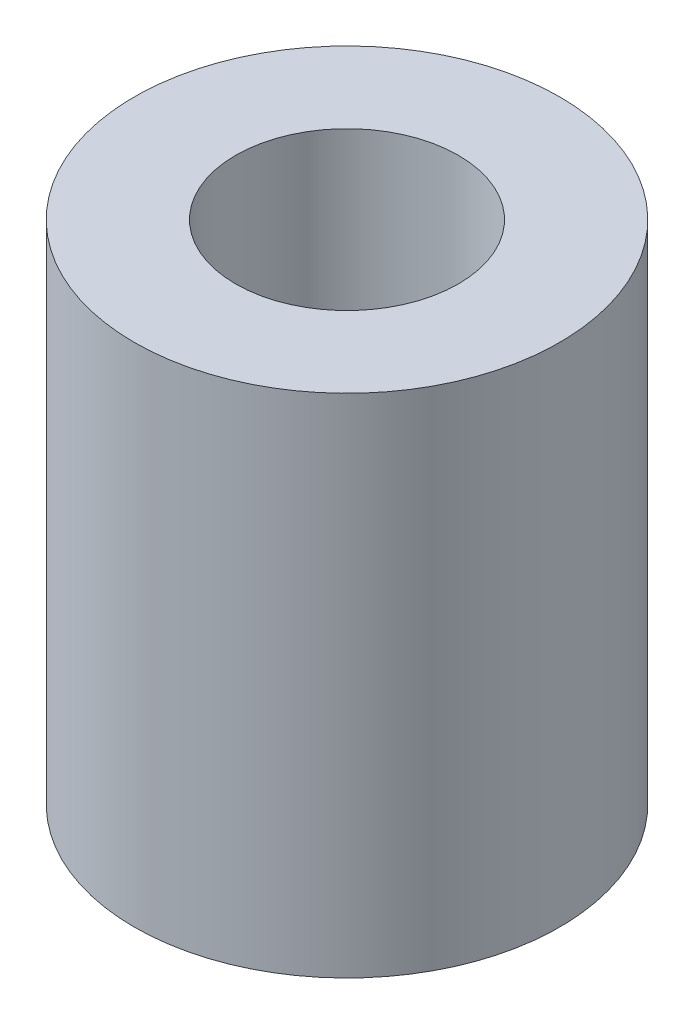
SolidWorks part; units mm, degrees
ref_plane "Front Plane" through (0, 0, 0) normal (0, 0, 1) x (1, 0, 0)
ref_plane "Top Plane" through (0, 0, 0) normal (0, 1, 0) x (1, 0, 0)
ref_plane "Right Plane" through (0, 0, 0) normal (1, 0, 0) x (0, 0, -1)
sketch "Sketch1" plane through (0, 0, 0) normal (0, 1, 0) x (1, 0, 0)
  circle A0 centre (0, 0) radius 1.1
  circle A1 centre (0, 0) radius 2.1
  dimension "D1" = 2.2
  dimension "D2" = 1
extrude "Boss-Extrude1" add sketch "Sketch1" along normal blind 5
